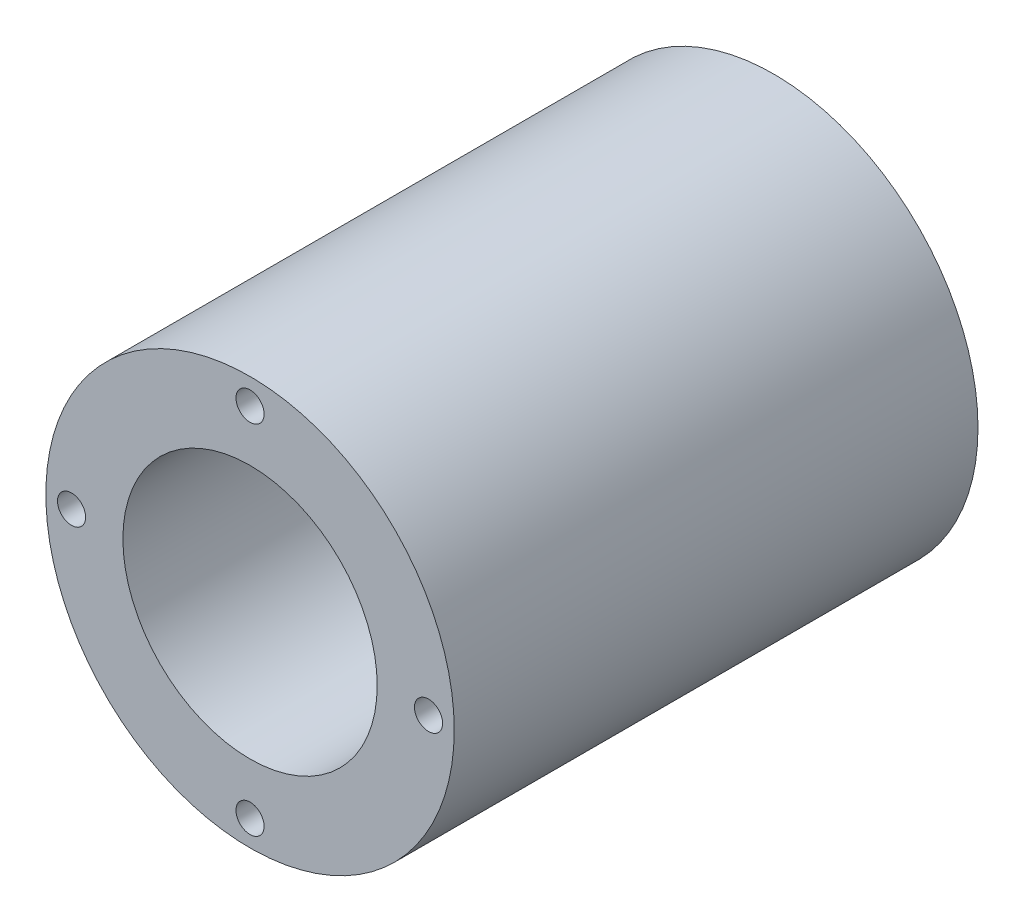
SolidWorks part; units mm, degrees
material "6061-T6 (SS)"
ref_plane "Front Plane" through (0, 0, 0) normal (0, 0, 1) x (1, 0, 0)
ref_plane "Top Plane" through (0, 0, 0) normal (0, 1, 0) x (1, 0, 0)
ref_plane "Right Plane" through (0, 0, 0) normal (1, 0, 0) x (0, 0, -1)
sketch "Sketch Spindle Skeleton" plane through (0, 0, 0) normal (1, 0, 0) x (0, 0, -1)
  line L0 (-95.847, -9.525) -> (-141.966, -9.525)
  line L5 (-1000, 0) -> (49000, 0)
  line L6 (0, -9.525) -> (0, 9.525)
  line L13 (0, 9.525) -> (-45.847, 9.525)
  line L26 (-45.847, 9.525) -> (-45.847, 12.7)
  line L27 (-45.847, 12.7) -> (-95.847, 12.7)
  line L32 (-95.847, 12.7) -> (-95.847, 9.525)
  line L34 (-160, 7) -> (-160, -7)
  line L36 (-95.847, -9.525) -> (-95.847, -12.7)
  line L37 (-95.847, -12.7) -> (-45.847, -12.7)
  line L38 (-45.847, -12.7) -> (-45.847, -9.525)
  line L39 (0, -9.525) -> (-45.847, -9.525)
  line L40 (-25.305, 36.322) -> (-16.305, 36.322)
  line L41 (-111.341, 22.6187) -> (-95.847, 22.6187)
  line L42 (-111.341, 22.6187) -> (-111.341, -22.6187)
  line L43 (-111.341, -22.6187) -> (-95.847, -22.6187)
  line L44 (-95.847, 22.6187) -> (-95.847, -22.6187)
  line L45 (-111.341, 22.6187) -> (-95.847, -22.6187) construction
  line L46 (-111.341, -22.6187) -> (-95.847, 22.6187) construction
  line L47 (-30.353, 22.6187) -> (-45.847, 22.6187)
  line L48 (-30.353, 22.6187) -> (-30.353, -22.6187)
  line L49 (-30.353, -22.6187) -> (-45.847, -22.6187)
  line L50 (-45.847, 22.6187) -> (-45.847, -22.6187)
  line L51 (-30.353, 22.6187) -> (-45.847, -22.6187) construction
  line L52 (-30.353, -22.6187) -> (-45.847, 22.6187) construction
  line L59 (-16.305, 36.322) -> (-16.305, -36.322)
  line L60 (-16.305, -36.322) -> (-25.305, -36.322)
  line L61 (-25.305, -22.6187) -> (-27.305, -22.6187)
  line L62 (-27.305, -22.6187) -> (-27.305, -12.5)
  line L63 (-27.305, -12.5) -> (-25.305, -12.5)
  line L64 (-25.305, -12.5) -> (-25.305, 12.5)
  line L65 (-25.305, 12.5) -> (-27.305, 12.5)
  line L66 (-27.305, 12.5) -> (-27.305, 22.6187)
  line L67 (-27.305, 22.6187) -> (-25.305, 22.6187)
  line L68 (-25.305, 22.6187) -> (-25.305, 36.322)
  line L69 (-25.305, -22.6187) -> (-25.305, -36.322)
  line L71 (-119.469, 36.322) -> (-26.305, 36.322)
  line L72 (-119.469, 36.322) -> (-119.469, -36.322)
  line L73 (-119.469, -36.322) -> (-26.305, -36.322)
  line L74 (-26.305, 36.322) -> (-26.305, -36.322)
  line L75 (-119.469, 36.322) -> (-26.305, -36.322) construction
  line L76 (-119.469, -36.322) -> (-26.305, 36.322) construction
  line L78 (-147.3, -7) -> (-160, -7)
  line L79 (-95.847, 9.525) -> (-141.966, 9.525)
  line L80 (-147.3, 7) -> (-160, 7)
  line L82 (-118.9065, 9.525) -> (-118.9065, -9.525) construction
  line L83 (-22.9235, 9.525) -> (-22.9235, -9.525) construction
  line L96 (-119.469, 36.322) -> (-134.709, 36.322)
  line L98 (-119.469, -36.322) -> (-134.709, -36.322)
  line L99 (-134.709, 36.322) -> (-134.709, -36.322)
  line L110 (-119.469, 36.322) -> (-119.469, -36.322)
  line L111 (-147.3, 7) -> (-147.3, 7.493)
  line L112 (-147.3, 7.493) -> (-141.966, 7.493)
  line L113 (-141.966, 7.493) -> (-141.966, 9.525)
  line L114 (-141.966, -9.525) -> (-141.966, -7.493)
  line L115 (-141.966, -7.493) -> (-147.3, -7.493)
  line L116 (-147.3, -7.493) -> (-147.3, -7)
  point P3 (0, 0)
  point P7 (0, 0)
  point P18 (-103.594, 0)
  point P24 (-38.1, 0)
  point P29 (-72.887, 0)
  point P48 (-16.305, 30.4704)
  point P70 (-134.709, 31.75)
sketch "Sketch1" plane through (0, 0, 0) normal (1, 0, 0) x (0, 0, -1)
  line L0 (-26.305, 36.322) -> (-26.305, -36.322) construction
  line L1 (-119.469, -36.322) -> (-26.305, -36.322) construction
  line L2 (-119.469, 36.322) -> (-119.469, -36.322) construction
  line L3 (-119.469, 36.322) -> (-26.305, 36.322) construction
  line L4 (-26.305, 36.322) -> (-26.305, -36.322)
  line L5 (-119.469, -36.322) -> (-26.305, -36.322)
  line L6 (-119.469, 36.322) -> (-119.469, -36.322)
  line L7 (-119.469, 36.322) -> (-26.305, 36.322)
  line L9 (-30.353, 22.6187) -> (-45.847, 22.6187) construction
  line L10 (-119.469, 22.6187) -> (-26.305, 22.6187)
  line L15 (-119.469, 0) -> (-26.305, 0) construction
revolve "Revolve1" add sketch "Sketch1" angle 360 about L15
sketch "Back Hole Top Location" plane through (0, 0, 26.305) normal (0, 0, -1) x (-1, 0, 0)
  point P1 (0, 30.4704)
  point P2 (0, 30.4704)
  point P7 (0, 0)
  point P9 (0, 30.4704)
hole_wizard "M6x1.0 Tapped Hole3" positions "Sketch8" profile "Sketch9" tap size "M6x1.0" standard "ANSI Metric"
sketch "Sketch8" plane through (0, 0, 26.305) normal (0, 0, -1) x (-1, 0, 0)
  point P3 (0, 30.4704)
sketch "Sketch9" plane through (0, 30.4704, 26.305) normal (1, 0, 0) x (0, 1, 0)
  line L0 (0, 0) -> (0, 16.4882)
  line L1 (0, 16.4882) -> (2.5, 14.986)
  line L2 (2.5, 14.986) -> (2.5, 0)
  line L5 (2.5, 0) -> (0, 0)
  line L10 (0, 16.4882) -> (-2.5, 14.986) construction
  line L11 (0, -6.35) -> (0, 107.95) construction
  dimension "Tap Drill Dia." = 5
  dimension "Tap Drill Depth" = 14.986
  dimension "Drill Angle" = 118
pattern_circular "BackFacePattern" count 6 over 360 about axis through (0, 0, 0) along (0, 0, 1) of "M6x1.0 Tapped Hole3"
ref_plane "Midplane" through (0, 0, 72.887) normal (0, 0, -1) x (-1, 0, 0)
sketch "Front Hole Top Location" plane through (0, 0, 119.469) normal (0, 0, 1) x (1, 0, 0)
  point P0 (0, 31.75)
  point P1 (0, 31.75)
  point P5 (0, 31.75)
hole_wizard "M6x1.0 Tapped Hole2" positions "Sketch5" profile "Sketch6" tap size "M6x1.0" standard "ANSI Metric"
sketch "Sketch5" plane through (0, 0, 119.469) normal (0, 0, 1) x (1, 0, 0)
  point P0 (0, 31.75)
sketch "Sketch6" plane through (0, 31.75, 119.469) normal (1, 0, 0) x (0, -1, 0)
  line L0 (0, 0) -> (0, 16.5022)
  line L1 (0, 16.5022) -> (2.5, 15)
  line L2 (2.5, 15) -> (2.5, 0)
  line L5 (2.5, 0) -> (0, 0)
  line L10 (0, 16.5022) -> (-2.5, 15) construction
  line L11 (0, -6.35) -> (0, 107.95) construction
  dimension "Tap Drill Dia." = 5
  dimension "Tap Drill Depth" = 15
  dimension "Drill Angle" = 118
pattern_circular "FrontFacePattern" count 4 over 360 about axis through (0, 0, 0) along (0, 0, 1) of "M6x1.0 Tapped Hole2"
sketch "Sketch7" plane through (0, 0, 26.305) normal (0, 0, -1) x (-1, 0, 0)
  circle A0 centre (0, 0) radius 26.9875
  circle A1 centre (0, 0) radius 24.6062
  dimension "D1" = 53.975
  dimension "D2" = 49.2125
extrude "Cut-Extrude1" cut sketch "Sketch7" against normal blind 0.5
